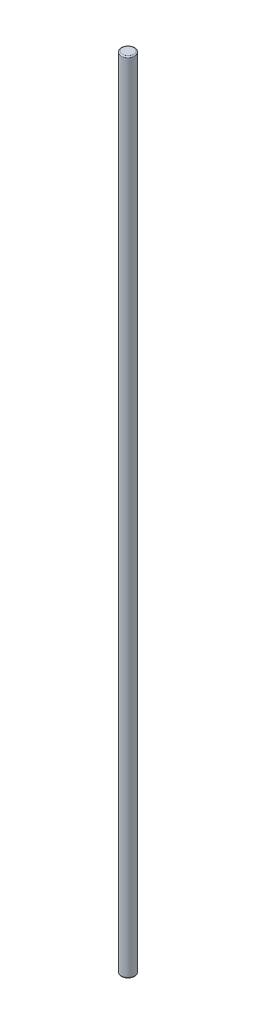
SolidWorks part; units mm, degrees
ref_plane "前视基准面" through (0, 0, 0) normal (0, 0, 1) x (1, 0, 0)
ref_plane "上视基准面" through (0, 0, 0) normal (0, 1, 0) x (1, 0, 0)
ref_plane "右视基准面" through (0, 0, 0) normal (1, 0, 0) x (0, 0, -1)
sketch "草图1" plane through (0, 0, 0) normal (0, 1, 0) x (1, 0, 0)
  circle A0 centre (0, 0) radius 3
  dimension "D1" = 6
extrude "凸台-拉伸1" add sketch "草图1" along normal blind 350
fillet "圆角1" radius 0.5 1 edges at (0, 0, 3)
fillet "圆角2" radius 0.5 1 edges at (0, 350, 3)
